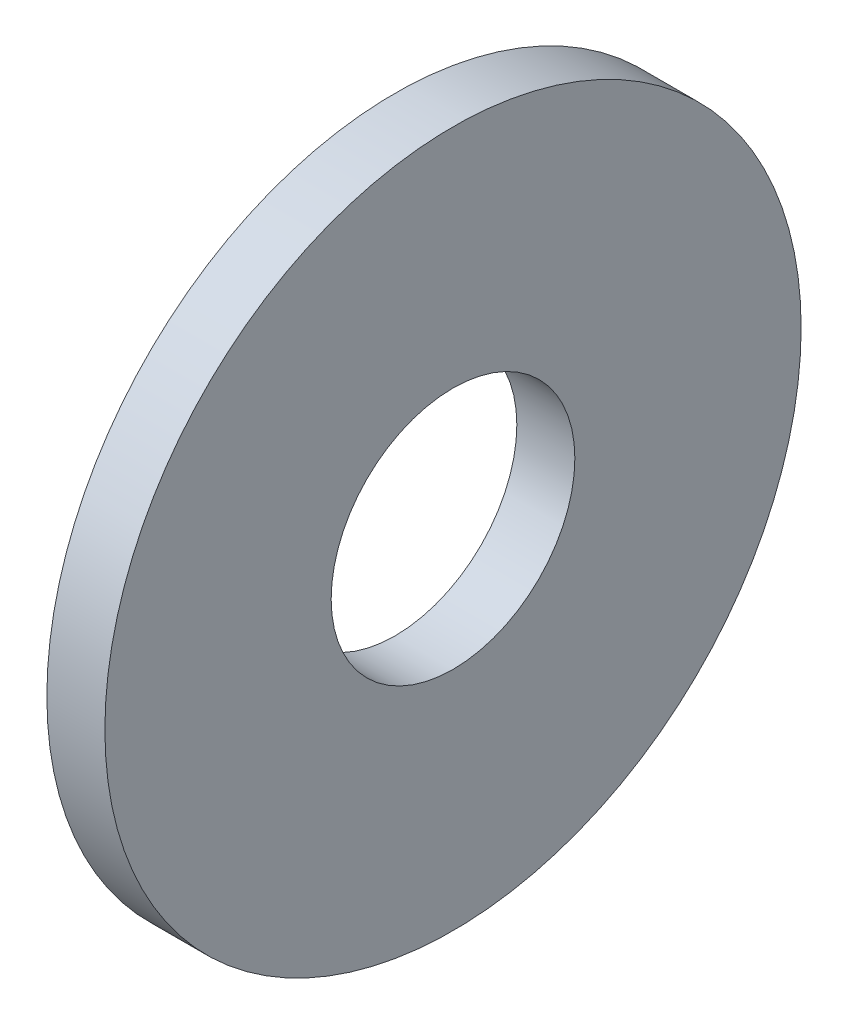
SolidWorks part; units mm, degrees
ref_plane "Plane1" through (0, 0, 0) normal (0, 0, 1) x (1, 0, 0)
ref_plane "Plane2" through (0, 0, 0) normal (0, 1, 0) x (1, 0, 0)
ref_plane "Plane3" through (0, 0, 0) normal (1, 0, 0) x (0, 0, -1)
sketch "Sketch1" plane through (0, 0, 0) normal (0, 0, 1) x (1, 0, 0)
  line L0 (-34.925, 0) -> (9.525, 0) construction
  line L1 (0, 5.25) -> (0, 15)
  line L2 (0, 15) -> (-2.5, 15)
  line L3 (-2.5, 15) -> (-2.5, 5.25)
  line L4 (-2.5, 5.25) -> (0, 5.25)
  dimension "Thickness" = 2.5
  dimension "Inside_dia" = 10.5
  dimension "Outside_dia" = 30
revolve "Base-Revolve" add sketch "Sketch1" angle 360 about L0
